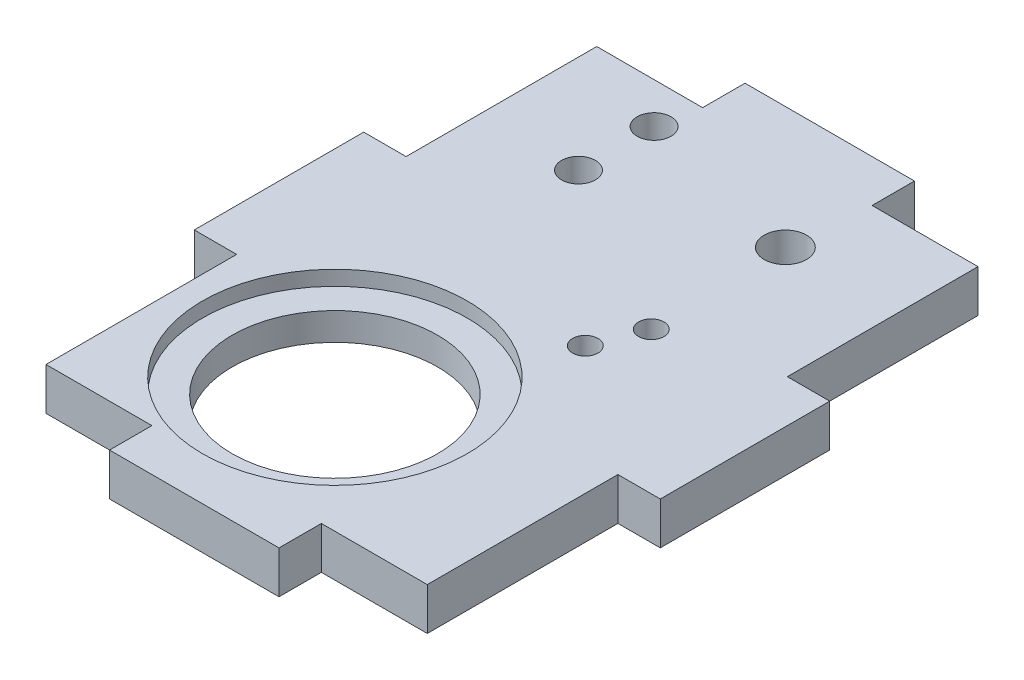
SolidWorks part; units mm, degrees
ref_plane "Front Plane" through (0, 0, 0) normal (0, 0, 1) x (1, 0, 0)
ref_plane "Top Plane" through (0, 0, 0) normal (0, 1, 0) x (1, 0, 0)
ref_plane "Right Plane" through (0, 0, 0) normal (1, 0, 0) x (0, 0, -1)
sketch "Sketch1" plane through (0, 0, 0) normal (0, 1, 0) x (1, 0, 0)
  line L1 (0, 0) -> (90, 0)
  line L2 (0, 0) -> (0, 130)
  line L3 (0, 130) -> (90, 130)
  line L4 (90, 0) -> (90, 130)
  line L5 (0, 85) -> (-10, 85)
  line L6 (0, 85) -> (0, 45)
  line L7 (0, 45) -> (-10, 45)
  line L8 (-10, 85) -> (-10, 45)
  line L9 (25, 130) -> (65, 130)
  line L10 (25, 130) -> (25, 140)
  line L11 (25, 140) -> (65, 140)
  line L12 (65, 130) -> (65, 140)
  line L13 (90, 85) -> (100, 85)
  line L14 (90, 85) -> (90, 45)
  line L15 (90, 45) -> (100, 45)
  line L16 (100, 85) -> (100, 45)
  line L17 (65, 0) -> (25, 0)
  line L18 (65, 0) -> (65, -10)
  line L19 (65, -10) -> (25, -10)
  line L20 (25, 0) -> (25, -10)
  point P21 (45, -10)
  point P22 (45, 140)
  point P23 (45, 0)
  point P24 (45, 130)
  point P25 (100, 65)
  point P26 (-10, 65)
  point P27 (90, 65)
  dimension "D1" = 90
  dimension "D2" = 130
  dimension "D3" = 10
  dimension "D4" = 10
  dimension "D5" = 10
  dimension "D6" = 10
  dimension "D7" = 40
  dimension "D8" = 40
  dimension "D9" = 40
  dimension "D10" = 40
extrude "Boss-Extrude1" add sketch "Sketch1" along normal blind 10 contours L1 L4 L3 L2 | L5 L8 L7 L2 | L16 L13 L4 L15 | L1 L20 L19 L18 | L11 L12 L9 L10
sketch "Sketch2" plane through (0, 10, 0) normal (0, 1, 0) x (1, 0, 0)
  line L0 (0, 102.57) -> (90.0901, 102.57) construction
  line L1 (65, 0) -> (90, 0) construction
  line L2 (23.1228, 98.57) -> (23.1228, 124.41) construction
  circle A0 centre (23.1228, 102.57) radius 4
  circle A1 centre (23.1228, 120.41) radius 4
  dimension "D2" = 8
  dimension "D4" = 8
  dimension "D1" = 102.57
  dimension "D3" = 25.84
extrude "Cut-Extrude1" cut sketch "Sketch2" against normal through all
sketch "Sketch3" plane through (0, 10, 0) normal (0, 1, 0) x (1, 0, 0)
  line L0 (80.2934, 67.48) -> (5.633, 67.48)
  line L1 (65, 0) -> (90, 0) construction
  line L2 (58.7227, 64.6909) -> (65.352, 81.4257)
  circle A0 centre (59.8276, 67.48) radius 3
  circle A1 centre (64.2471, 78.6365) radius 3
  dimension "D2" = 6
  dimension "D4" = 6
  dimension "D1" = 67.48
  dimension "D3" = 18
extrude "Cut-Extrude2" cut sketch "Sketch3" against normal through all contours L2 A1 | L2 A1 | L0 A0 L2 | L2 A0 L0 | L0 A0 L2 | L2 A0 L0
sketch "Sketch4" plane through (0, 10, 0) normal (0, 1, 0) x (1, 0, 0)
  line L0 (0, 0) -> (0, 45) construction
  line L1 (65, 0) -> (90, 0) construction
  circle A0 centre (36.72, 31.47) radius 31.25
  dimension "D3" = 62.5
  dimension "D1" = 36.72
  dimension "D2" = 31.47
extrude "Cut-Extrude3" cut sketch "Sketch4" against normal blind 3.5
sketch "Sketch5" plane through (0, 6.5, 0) normal (0, 1, 0) x (1, 0, 0)
  circle A3 centre (36.72, 31.47) radius 24.25
  circle A4 centre (36.72, 31.47) radius 24.25
  dimension "D1" = 7
extrude "Cut-Extrude4" cut sketch "Sketch5" against normal through all
sketch "Sketch6" plane through (0, 10, 0) normal (0, 1, 0) x (1, 0, 0)
  circle A0 centre (63.3149, 111.2096) radius 5
  dimension "D1" = 10
extrude "Cut-Extrude5" cut sketch "Sketch6" against normal through all
